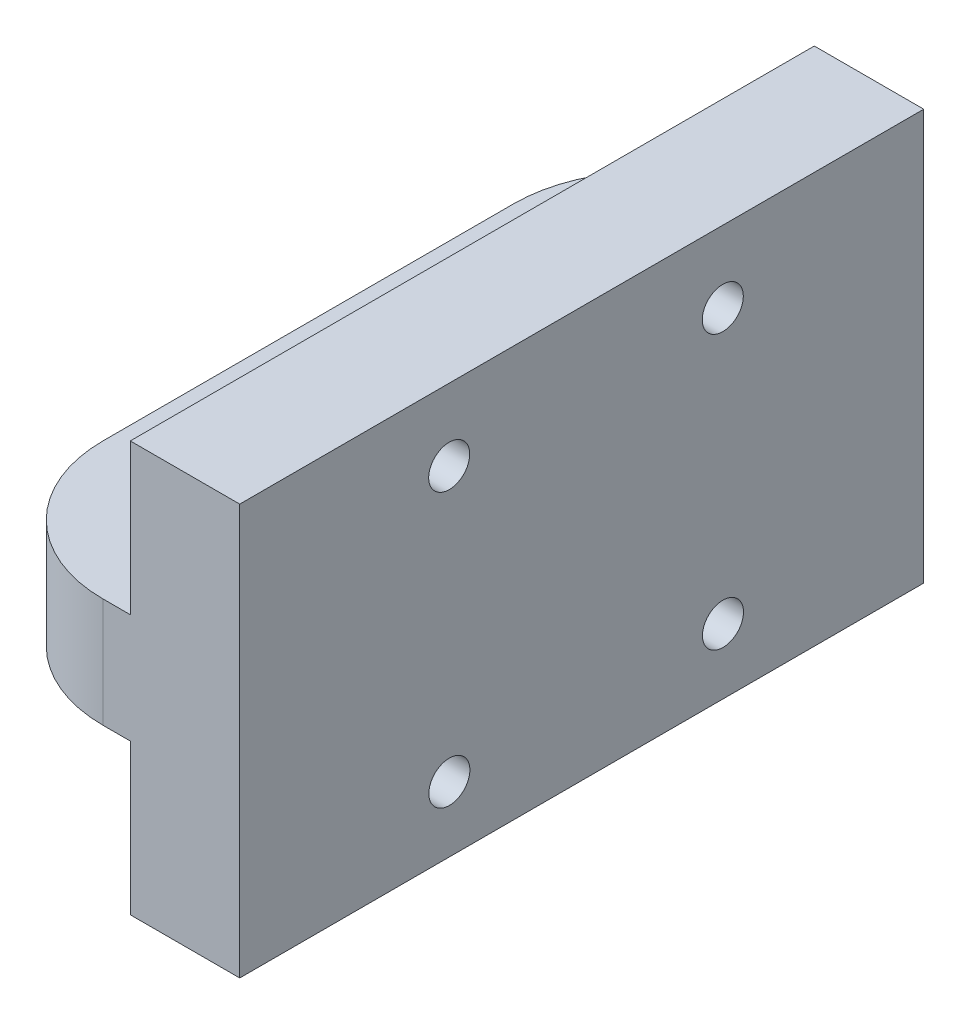
SolidWorks part; units mm, degrees
ref_plane "Front Plane" through (0, 0, 0) normal (0, 0, 1) x (1, 0, 0)
ref_plane "Top Plane" through (0, 0, 0) normal (0, 1, 0) x (1, 0, 0)
ref_plane "Right Plane" through (0, 0, 0) normal (1, 0, 0) x (0, 0, -1)
sketch "Sketch1" plane through (0, 0, 0) normal (0, 1, 0) x (1, 0, 0)
  line L1 (0, 0) -> (20, 0)
  line L2 (0, 0) -> (0, 50)
  line L3 (0, 50) -> (20, 50)
  line L4 (20, 0) -> (20, 50)
  dimension "D1" = 20
  dimension "D2" = 50
extrude "Boss-Extrude1" add sketch "Sketch1" along normal blind 8
fillet "Fillet1" radius 10 2 edges at (0, 4, -50) (0, 4, 0)
sketch "Sketch2" plane through (20, 0, 0) normal (1, 0, 0) x (0, 0, -1)
  line L0 (0, 8) -> (0, 0) construction
  line L1 (0, 19) -> (50, 19)
  line L2 (0, 19) -> (0, -11)
  line L3 (0, -11) -> (50, -11)
  line L4 (50, 19) -> (50, -11)
  point P5 (99.9098, 8)
  point P6 (97.9248, 16.2112)
  point P9 (0, 4)
  dimension "D1" = 50
  dimension "D2" = 30
extrude "Boss-Extrude2" add sketch "Sketch2" against normal blind 8
sketch "Sketch3" plane through (20, 0, 0) normal (1, 0, 0) x (0, 0, -1)
  circle A0 centre (15.312, 13.7606) radius 1.5
  circle A1 centre (15.3243, -6.2394) radius 1.5
  circle A2 centre (35.312, 13.7606) radius 1.5
  circle A3 centre (35.3243, -6.2394) radius 1.5
  point P4 (0, 0)
  point P5 (0, 0)
  point P10 (0, 0)
  point P11 (0, 0)
  point P12 (0, 0)
  dimension "D1" = 3
  dimension "D2" = 3
  dimension "D3" = 20
  dimension "D4" = 2
extrude "Cut-Extrude1" cut sketch "Sketch3" against normal blind 8
